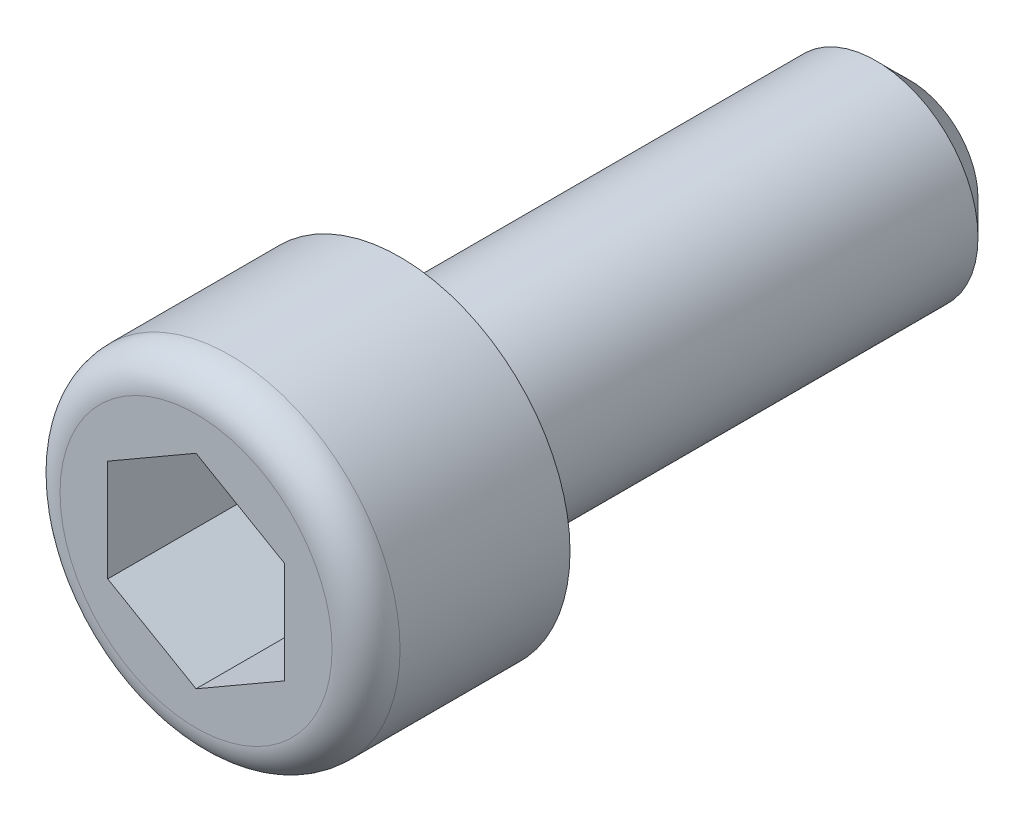
SolidWorks part; units mm, degrees
ref_plane "Front Plane" through (0, 0, 0) normal (0, 0, 1) x (1, 0, 0)
ref_plane "Top Plane" through (0, 0, 0) normal (0, 1, 0) x (1, 0, 0)
ref_plane "Right Plane" through (0, 0, 0) normal (1, 0, 0) x (0, 0, -1)
sketch "Sketch1" plane through (0, 0, 0) normal (1, 0, 0) x (0, 0, -1)
  line L0 (-156.2916, 0) -> (7658.2872, 0) construction
  line L1 (0, 0) -> (0, 5)
  line L2 (0, 5) -> (6, 5)
  line L3 (6, 5) -> (6, 3)
  line L4 (6, 3) -> (21, 3)
  line L5 (21, 3) -> (21, 0)
  line L6 (21, 0) -> (0, 0)
  dimension "D1" = 6
  dimension "D2" = 15
  dimension "D3" = 6
  dimension "D4" = 10
revolve "Body" add sketch "Sketch1" angle 360 about L0
sketch "Sketch2" plane through (0, 0, 0) normal (0, 0, 1) x (1, 0, 0)
  line L1 (0, 3) -> (-2.5981, 1.5)
  line L2 (-2.5981, 1.5) -> (-2.5981, -1.5)
  line L3 (-2.5981, -1.5) -> (0, -3)
  line L4 (0, -3) -> (2.5981, -1.5)
  line L5 (2.5981, -1.5) -> (2.5981, 1.5)
  line L6 (2.5981, 1.5) -> (0, 3)
  circle A0 centre (0, 0) radius 3 construction
  dimension "D1" = 6
extrude "Footprint" cut sketch "Sketch2" against normal blind 4.5
chamfer "Chamfer1" distance 1 angle 45 1 edges at (3, 0, -21)
fillet "Fillet1" radius 1 1 edges at (5, 0, 0)
